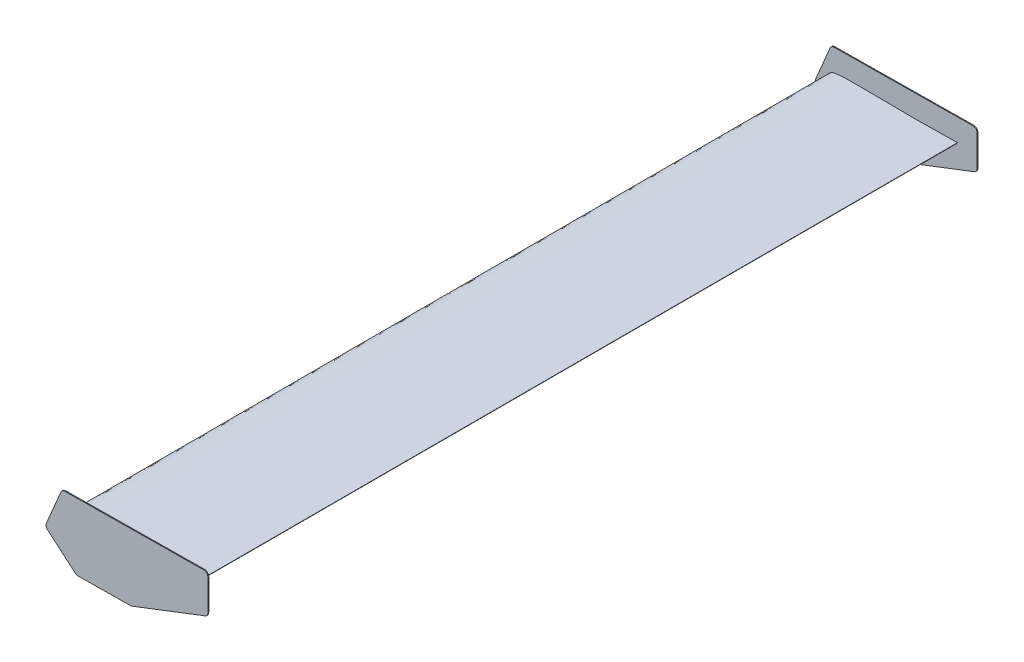
SolidWorks part; units mm, degrees
ref_plane "Front Plane" through (0, 0, 0) normal (0, 0, 1) x (1, 0, 0)
ref_plane "Top Plane" through (0, 0, 0) normal (0, 1, 0) x (1, 0, 0)
ref_plane "Right Plane" through (0, 0, 0) normal (1, 0, 0) x (0, 0, -1)
curve "Airfoil Curve"
  spline degree 3 poles (300, -0.39, 0) (295.0052, -1.7497, 0) (285.0396, -4.4626, 0) (265.0756, -9.3952, 0) (240.11, -14.8452, 0) (210.0811, -20.2176, 0) (180.0755, -24.6212, 0) (150.0532, -27.7624, 0) (120.0335, -29.7214, 0) (94.9726, -29.7413, 0) (74.963, -28.3569, 0) (59.9355, -26.5335, 0) (44.8755, -23.8445, 0) (32.3958, -20.6106, 0) (22.3952, -17.3445, 0) (14.8545, -14.2611, 0) (8.4203, -10.9265, 0) (2.8355, -6.9378, 0) (-2.0261, -0.5226, 0) (3.2214, 4.3836, 0) (8.5759, 6.3095, 0) (14.9528, 7.6093, 0) (22.4839, 8.2702, 0) (32.4958, 8.738, 0) (45.0031, 8.7029, 0) (60.0065, 8.2831, 0) (74.9993, 7.4837, 0) (94.9994, 6.5483, 0) (119.9952, 5.3479, 0) (150.0009, 4.2208, 0) (179.9969, 2.9692, 0) (209.9958, 1.9031, 0) (239.9971, 1.119, 0) (264.9992, 0.7209, 0) (284.9995, 0.4587, 0) (294.9999, 0.4129, 0) (300, 0.39, 0) knots 0 0 0 0 0.025305 0.050488 0.10052 0.150191 0.199587 0.24874 0.297716 0.346601 0.371103 0.395726 0.42057 0.445825 0.458702 0.47192 0.485786 0.493461 0.506863 0.516148 0.522766 0.535269 0.547551 0.559786 0.584229 0.608681 0.633151 0.657622 0.706558 0.755482 0.804406 0.85332 0.902221 0.951113 0.975557 1 1 1 1
ref_plane "Plane1" through (300, -0.39, 0) normal (-0.9649, -0.2627, 0) x (0, 0, 1)
sketch "AirfoilSketch" plane through (0, 0, 0) normal (0, 0, 1) x (1, 0, 0)
  line L2 (0, 0) -> (350.3559, 0) construction
  line B0 (299.8175, 10.4699) -> (299.8437, 9.6903)
  line B1 (0, 0) -> (299.8175, 10.4699) construction
  spline B2 degree 3 poles (299.8437, 9.6903) (294.8974, 8.1635) (285.0286, 5.1174) (265.2416, -0.4833) (240.4732, -6.769) (210.6418, -13.1474) (180.8011, -18.5567) (150.9013, -22.7049) (120.9643, -25.6715) (95.9183, -26.5334) (75.8735, -25.8221) (60.7932, -24.5047) (45.6513, -22.3232) (33.07, -19.5104) (22.9653, -16.5822) (15.3253, -13.7539) (8.7827, -10.6374) (3.067, -6.8386) (-2.0074, -0.5904) (3.0723, 4.4894) (8.3591, 6.5941) (14.6887, 8.1075) (22.1934, 9.021) (32.1839, 9.8249) (44.6853, 10.2101) (59.6943, 10.2946) (74.7055, 9.9994) (94.7257, 9.7366) (119.7478, 9.3768) (149.7743, 9.2585) (179.7955, 9.0154) (209.8132, 8.958) (239.8239, 9.1823) (264.8254, 9.6245) (284.8232, 10.0345) (294.8195, 10.3247) (299.8175, 10.4699) knots 0 0 0 0 0.025305 0.050488 0.10052 0.150191 0.199587 0.24874 0.297716 0.346601 0.371103 0.395726 0.42057 0.445825 0.458702 0.47192 0.485786 0.493461 0.506863 0.516148 0.522766 0.535269 0.547551 0.559786 0.584229 0.608681 0.633151 0.657622 0.706558 0.755482 0.804406 0.85332 0.902221 0.951113 0.975557 1 1 1 1
  dimension "AoA_Rear_Wing" = 2
sketch_block_instance "AirfoilBlock-1"
sketch_block "AirfoilBlock"
extrude "Rear Wing" add sketch "AirfoilSketch" along normal mid plane 1800
sketch "Endplate Sketch" plane through (0, 0, 900) normal (0, 0, 1) x (1, 0, 0)
  line L0 (4.1984, 59.4067) -> (-35.2909, -33.8505)
  line L1 (-35.2909, -33.8505) -> (38.2575, -96.7338)
  line L2 (4.1984, 59.4067) -> (345.6673, 62.9082)
  line L3 (345.6673, 62.9082) -> (345.6673, -26.3186)
  line L5 (38.2575, -96.7338) -> (166.2751, -95.4211)
  line L6 (166.2751, -95.4211) -> (345.6673, -26.3186)
  point P2 (152.1224, -101.9226)
  point P6 (313.3454, 63.1358)
  point P7 (345.6673, -26.3186)
  point P8 (345.6673, 62.9082)
  point P9 (4.1984, 59.4067)
  point P10 (-35.2909, -33.8505)
extrude "Endplate" add sketch "Endplate Sketch" along normal mid plane 2
fillet "Endplate Fillet" radius 10 6 edges at (345.6673, 62.9082, 900) (345.6673, -26.3186, 900) (166.2751, -95.4211, 900) (4.1984, 59.4067, 900) (-35.2909, -33.8505, 900) (38.2575, -96.7338, 900)
mirror "Mirror3" about plane through (0, 0, 0) normal (0, 0, 1) of "Endplate Fillet", "Endplate"
